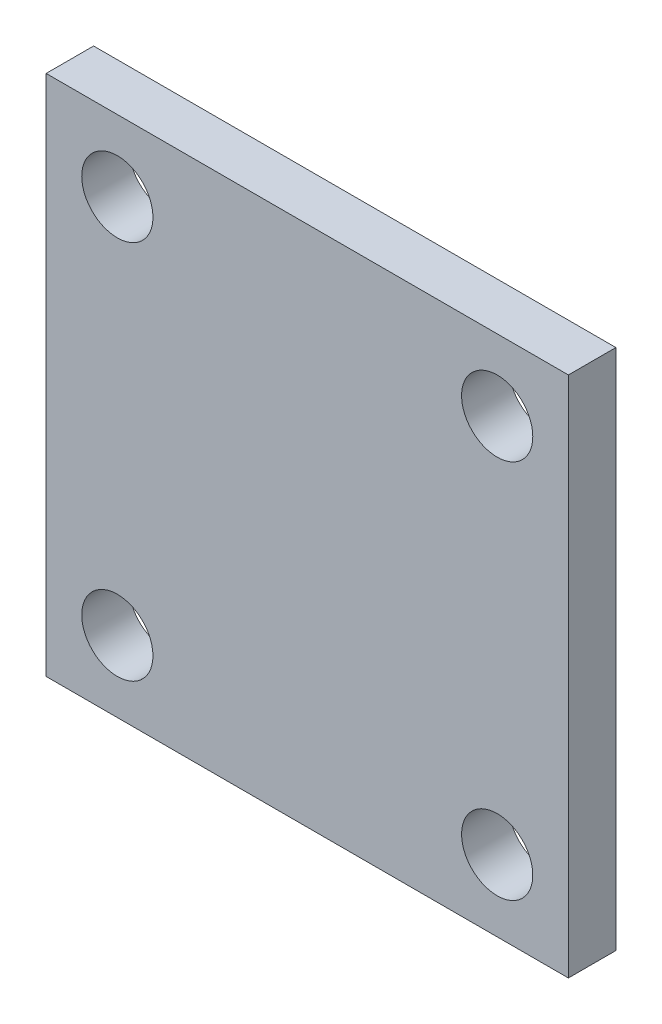
SolidWorks part; units mm, degrees
ref_plane "Ebene vorne" through (0, 0, 0) normal (0, 0, 1) x (1, 0, 0)
ref_plane "Ebene oben" through (0, 0, 0) normal (0, 1, 0) x (1, 0, 0)
ref_plane "Ebene rechts" through (0, 0, 0) normal (1, 0, 0) x (0, 0, -1)
sketch "Sketch1" plane through (0, 0, 0) normal (0, 0, 1) x (1, 0, 0)
  line L0 (55, 0) -> (-55, 0) construction
  line L1 (-11, -11) -> (11, -11)
  line L2 (-11, -11) -> (-11, 11)
  line L3 (-11, 11) -> (11, 11)
  line L4 (11, -11) -> (11, 11)
  line L5 (-11, -11) -> (11, 11) construction
  line L6 (-11, 11) -> (11, -11) construction
  line L7 (0, -55) -> (0, 55) construction
  circle A0 centre (8, 8) radius 1.5
  circle A1 centre (8, -8) radius 1.5
  circle A2 centre (-8, -8) radius 1.5
  circle A3 centre (-8, 8) radius 1.5
  point P0 (0, 0)
  dimension "D3" = 3
  dimension "D1" = 22
  dimension "D2" = 22
  dimension "D4" = 8
  dimension "D5" = 8
extrude "Boss-Extrude1" add sketch "Sketch1" along normal blind 2
